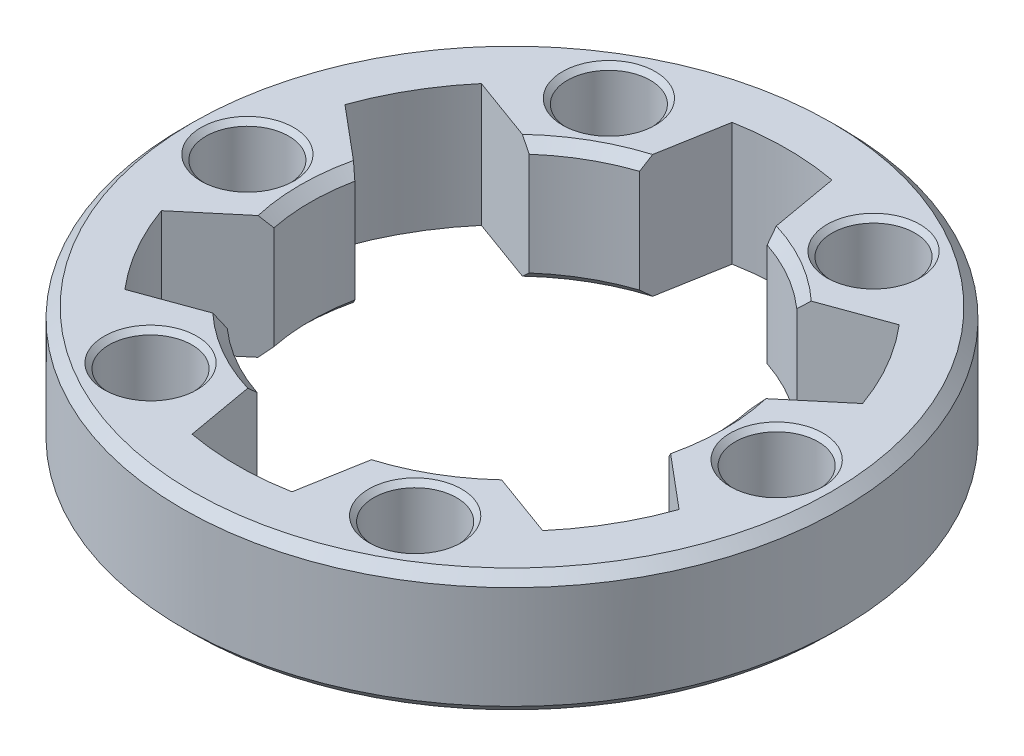
SolidWorks part; units mm, degrees
ref_plane "Plano frontal" through (0, 0, 0) normal (0, 0, 1) x (1, 0, 0)
ref_plane "Plano superior" through (0, 0, 0) normal (0, 1, 0) x (1, 0, 0)
ref_plane "Plano direito" through (0, 0, 0) normal (1, 0, 0) x (0, 0, -1)
sketch "Esboço1" plane through (0, 0, 0) normal (0, 0, 1) x (1, 0, 0)
  line L0 (0, -47.9778) -> (0, 47.3294) construction
  line L2 (33, 0) -> (20.2, 0)
  line L3 (33, 0) -> (33, 12.3)
  line L4 (33, 12.3) -> (20.2, 12.3)
  line L5 (20.2, 0) -> (20.2, 12.3)
  dimension "D1" = 20.2
  dimension "D2" = 12.3
  dimension "D3" = 33
revolve "Revolução1" add sketch "Esboço1" angle 360 about L0
chamfer "Chanfro1" distance 1 angle 45 4 edges at (0, 0, -33) (0, 12.3, -33) (0, 0, -20.2) (0, 12.3, -20.2)
sketch "Esboço2" plane through (0, 12.3, 0) normal (0, 1, 0) x (1, 0, 0)
  line L0 (0, 0) -> (0, 20.2) construction
  line L1 (20.9187, 17.8509) -> (10.0582, 13.898)
  line L2 (-5, 27.0416) -> (-7.0069, 15.6597)
  line L3 (5, 27.0416) -> (7.0069, 15.6597)
  line L4 (-7.0069, 15.6597) -> (7.0069, 15.6597)
  line L5 (25.9187, 9.1907) -> (17.0652, 1.7617)
  line L6 (10.0582, 13.898) -> (17.0652, 1.7617)
  line L7 (25.9187, -9.1907) -> (17.0652, -1.7617)
  line L8 (20.9187, -17.8509) -> (10.0582, -13.898)
  line L9 (17.0652, -1.7617) -> (10.0582, -13.898)
  line L10 (5, -27.0416) -> (7.0069, -15.6597)
  line L11 (-5, -27.0416) -> (-7.0069, -15.6597)
  line L12 (7.0069, -15.6597) -> (-7.0069, -15.6597)
  line L13 (-20.9187, -17.8509) -> (-10.0582, -13.898)
  line L14 (-25.9187, -9.1907) -> (-17.0652, -1.7617)
  line L15 (-10.0582, -13.898) -> (-17.0652, -1.7617)
  line L16 (-25.9187, 9.1907) -> (-17.0652, 1.7617)
  line L17 (-20.9187, 17.8509) -> (-10.0582, 13.898)
  line L18 (-17.0652, 1.7617) -> (-10.0582, 13.898)
  circle A0 centre (0, 0) radius 20.2 construction
  arc A1 (20.9187, 17.8509) -> (25.9187, 9.1907) centre (0, 0) cw
  arc A2 (-5, 27.0416) -> (5, 27.0416) centre (0, 0) cw
  arc A3 (25.9187, -9.1907) -> (20.9187, -17.8509) centre (0, 0) cw
  arc A4 (5, -27.0416) -> (-5, -27.0416) centre (0, 0) cw
  arc A5 (-20.9187, -17.8509) -> (-25.9187, -9.1907) centre (0, 0) cw
  arc A6 (-25.9187, 9.1907) -> (-20.9187, 17.8509) centre (0, 0) cw
  dimension "D1" = 6
extrude "Corte-extrusão1" cut sketch "Esboço2" against normal through all
sketch "Esboço3" plane through (0, 12.3, 0) normal (0, 1, 0) x (1, 0, 0)
  circle A0 centre (0, 0) radius 26.5 construction
  circle A1 centre (-26.5, 0) radius 4.15
  circle A2 centre (-13.25, 22.9497) radius 4.15
  circle A3 centre (13.25, 22.9497) radius 4.15
  circle A4 centre (26.5, 0) radius 4.15
  circle A5 centre (13.25, -22.9497) radius 4.15
  circle A6 centre (-13.25, -22.9497) radius 4.15
  dimension "D1" = 53
  dimension "D2" = 8.3
  dimension "D3" = 6
extrude "Corte-extrusão2" cut sketch "Esboço3" against normal through all
chamfer "Chanfro2" distance 0.5 angle 45 12 edges at (-26.5, 0, 4.15) (-26.5, 12.3, 4.15) (-13.25, 0, 27.0997) (-13.25, 12.3, 27.0997) (13.25, 0, 27.0997) (13.25, 12.3, 27.0997) (26.5, 0, 4.15) (26.5, 12.3, 4.15) (13.25, 0, -18.7997) (13.25, 12.3, -18.7997) (-13.25, 0, -18.7997) (-13.25, 12.3, -18.7997)
